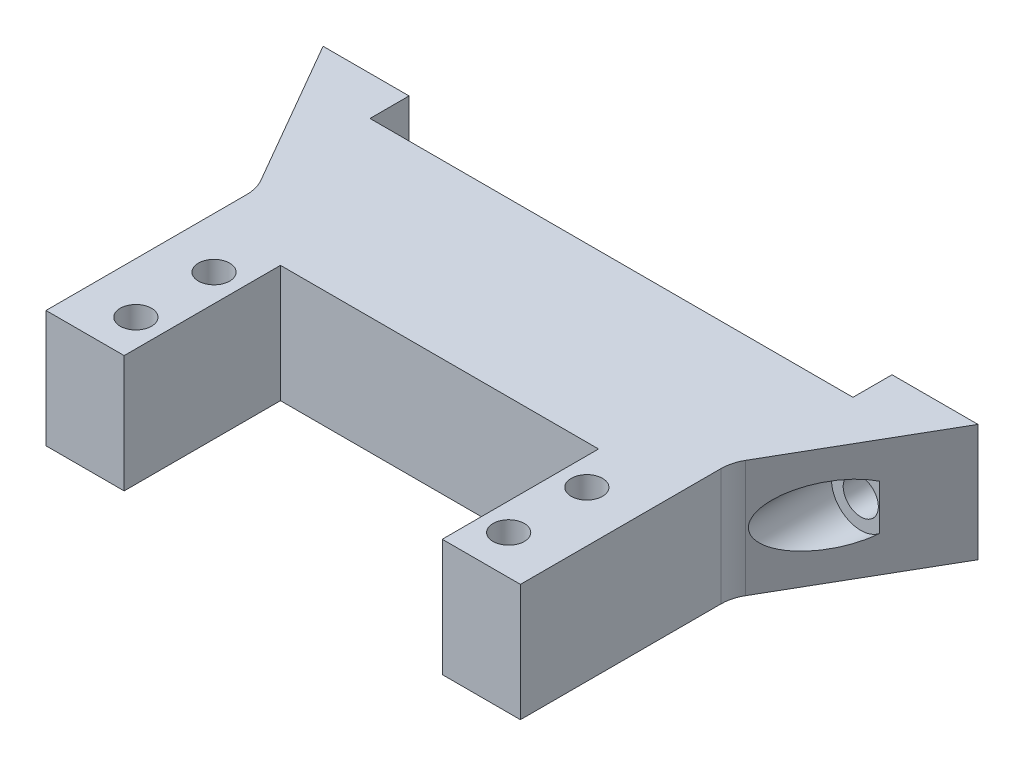
SolidWorks part; units mm, degrees
ref_plane "Front Plane" through (0, 0, 0) normal (1, 0, 0) x (0, 1, 0)
ref_plane "Top Plane" through (0, 0, 0) normal (0, 0, 1) x (0, 1, 0)
ref_plane "Right Plane" through (0, 0, 0) normal (0, 1, 0) x (-1, 0, 0)
sketch "Sketch1" plane through (0, 0, 0) normal (0, 1, 0) x (-1, 0, 0)
  line L0 (0, 15.9216) -> (0, -10) construction
  line L1 (20.35, 10) -> (-20.35, 10) construction
  line L2 (20.35, 10) -> (20.35, -10) construction
  line L3 (20.35, -10) -> (-20.35, -10) construction
  line L4 (-20.35, 10) -> (-20.35, -10) construction
  line L5 (20.35, 10) -> (-20.35, -10) construction
  line L6 (20.35, -10) -> (-20.35, 10) construction
  line L7 (20.35, 10) -> (20.35, -10)
  line L8 (20.35, -10) -> (-20.35, -10)
  line L9 (-20.35, -10) -> (-20.35, 10)
  line L10 (20.35, 10) -> (30.35, 10)
  line L11 (30.35, 10) -> (30.35, -15.6603)
  line L12 (-20.35, 10) -> (-30.35, 10)
  line L13 (-30.35, 10) -> (-30.35, -15.6603)
  line L14 (31.0199, -18.1603) -> (41.897, -37)
  line L15 (-31.0199, -18.1603) -> (-41.897, -37)
  line L16 (-41.897, -37) -> (41.897, -37)
  arc A0 (30.35, -15.6603) -> (31.0199, -18.1603) centre (35.35, -15.6603) ccw
  arc A1 (-30.35, -15.6603) -> (-31.0199, -18.1603) centre (-35.35, -15.6603) cw
  circle A2 centre (23.85, -5) radius 2
  circle A3 centre (23.85, 5) radius 2
  circle A4 centre (-23.85, -5) radius 2
  circle A5 centre (-23.85, 5) radius 2
  point P0 (0, 0)
  point P15 (30.35, -17)
  dimension "D7" = 5
  dimension "D8" = 4
  dimension "D1" = 40.7
  dimension "D2" = 20
  dimension "D3" = 10
  dimension "D4" = 27
  dimension "D5" = 150
  dimension "D6" = 20
  dimension "D9" = 3.5
  dimension "D10" = 10
  dimension "D11" = 5
extrude "Boss-Extrude1" add sketch "Sketch1" against normal blind 15
sketch "Sketch2" plane through (0, 0, -37) normal (0, 0, -1) x (1, 0, 0)
  line L0 (-41.897, 7.5) -> (41.897, 7.5) construction
  line L1 (-41.897, 15) -> (-41.897, 0) construction
  line L2 (41.897, 15) -> (41.897, 0) construction
  line L3 (0, -8.25) -> (0, 8.25) construction
  circle A0 centre (-34.897, 7.5) radius 2.25
  circle A1 centre (34.897, 7.5) radius 2.25
  dimension "D1" = 4.5
  dimension "D2" = 7
extrude "Cut-Extrude1" cut sketch "Sketch2" against normal blind 8
ref_plane "Plane1" through (0, 0, -29) normal (0, 0, -1) x (-1, 0, 0)
sketch "Sketch3" plane through (0, 0, -29) normal (0, 0, -1) x (-1, 0, 0)
  line L0 (0, 8.25) -> (0, -8.25) construction
  circle A0 centre (-34.897, -7.5) radius 3.75
  circle A1 centre (34.897, -7.5) radius 3.75
  dimension "D1" = 7.5
extrude "Cut-Extrude2" cut sketch "Sketch3" against normal through all
sketch "Sketch4" plane through (0, -15, 0) normal (0, -1, 0) x (1, 0, 0)
  line L0 (41.897, -37) -> (30.897, -37) construction
  line L1 (30.897, -37) -> (30.897, -32)
  line L2 (0, -8.25) -> (0, 8.25) construction
  line L3 (41.897, -37) -> (-41.897, -37) construction
  line L5 (-41.897, -37) -> (-30.897, -37) construction
  line L6 (-30.897, -37) -> (-30.897, -32)
  line L7 (-30.897, -32) -> (30.897, -32)
  line L8 (-30.897, -37) -> (30.897, -37)
  dimension "D1" = 11
  dimension "D2" = 5
extrude "Cut-Extrude3" cut sketch "Sketch4" against normal through all
